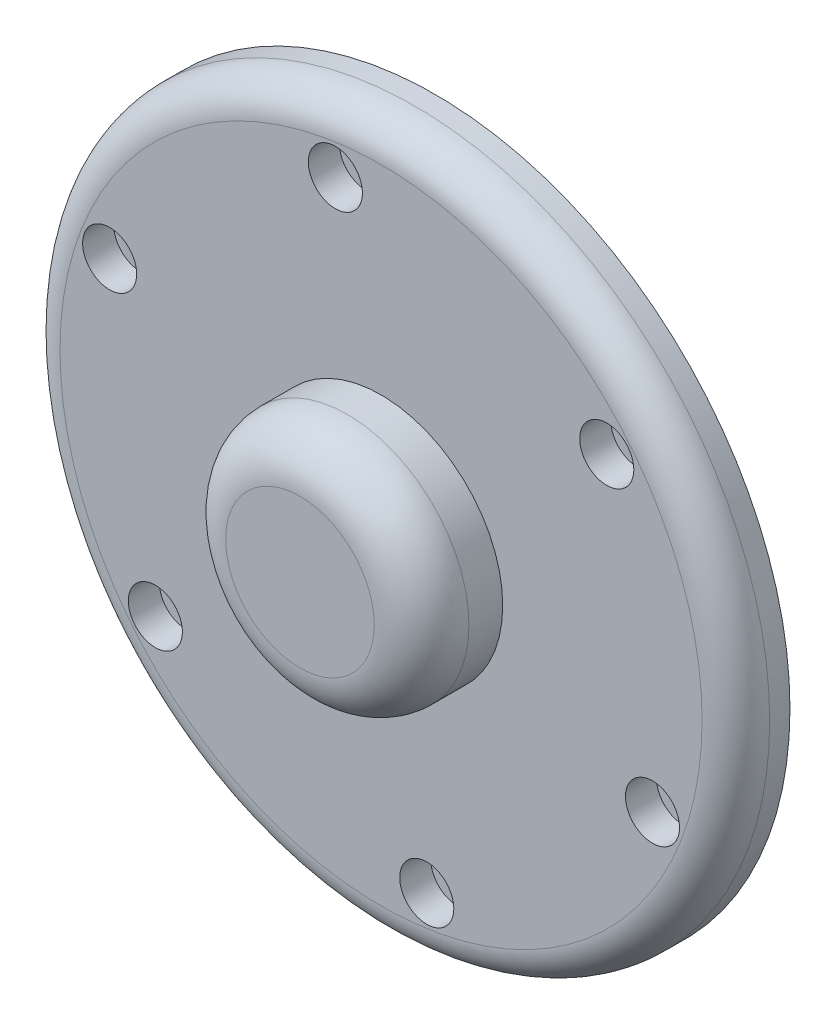
SolidWorks part; units mm, degrees
ref_plane "前视基准面" through (0, 0, 0) normal (0, 0, 1) x (1, 0, 0)
ref_plane "上视基准面" through (0, 0, 0) normal (0, 1, 0) x (1, 0, 0)
ref_plane "右视基准面" through (0, 0, 0) normal (1, 0, 0) x (0, 0, -1)
other "Configuration Table"
sketch "草图1" plane through (0, 0, 0) normal (0, 0, 1) x (1, 0, 0)
  circle A0 centre (0, 0) radius 52.5
  dimension "D1" = 105
extrude "凸台-拉伸1" add sketch "草图1" along normal blind 20
sketch "草图3" plane through (0, 0, 20) normal (0, 0, 1) x (1, 0, 0)
  circle A0 centre (0, 0) radius 52.5
  circle A2 centre (0, 0) radius 18
  dimension "D1" = 105
  dimension "D3" = 36
extrude "切除-拉伸1" cut sketch "草图3" against normal blind 12
sketch "草图5" plane through (0, 0, 0) normal (0, 0, -1) x (-1, 0, 0)
  line L0 (0, 11) -> (0, -11) construction
  circle A0 centre (0, 0.6473) radius 15.25
  dimension "D1" = 30.5
extrude "切除-拉伸3" cut sketch "草图5" against normal blind 17.5
hole_wizard "M4 六角圆柱头螺钉的柱形沉头孔1" positions "草图12" profile "草图13" counterbore size "M4" standard "GB" end condition through all
sketch "草图12" plane through (0, 0, 8) normal (0, 0, 1) x (1, 0, 0)
  point P0 (33.3945, 27.0889)
sketch "草图13" plane through (33.3945, 27.0889, 8) normal (1, 0, 0) x (0, -1, 0)
  line L0 (0, 0) -> (0, 8)
  line L1 (0, 8) -> (2.25, 8)
  line L3 (2.25, 8) -> (2.25, 4.6)
  line L4 (2.25, 4.6) -> (4, 4.6)
  line L5 (4, 4.6) -> (4, 0)
  line L7 (4, 0) -> (0, 0)
  line L11 (0, -6.35) -> (0, 107.95) construction
  dimension "通孔孔直径" = 4.5
  dimension "通孔孔深度" = 8
  dimension "柱形沉头孔直径" = 8
  dimension "柱形沉头孔深度" = 4.6
pattern_circular "阵列(圆周)1" count 6 over 360 about axis through (0, 0, 0) along (0, 0, 1) of "M4 六角圆柱头螺钉的柱形沉头孔1"
fillet "圆角2" radius 7 1 edges at (18, 0, 20)
fillet "圆角3" radius 5 1 edges at (52.5, 0, 8)
